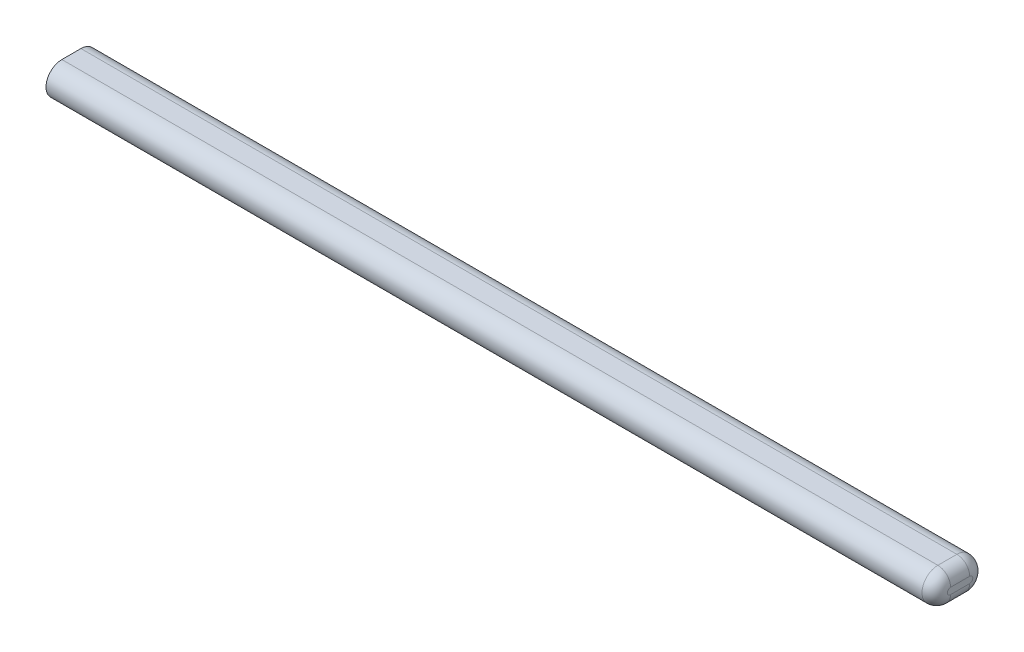
SolidWorks part; units mm, degrees
material "Mahogany"
ref_plane "Front Plane" through (0, 0, 0) normal (0, 0, 1) x (1, 0, 0)
ref_plane "Top Plane" through (0, 0, 0) normal (0, 1, 0) x (1, 0, 0)
ref_plane "Right Plane" through (0, 0, 0) normal (1, 0, 0) x (0, 0, -1)
sketch "Sketch2" plane through (0, 0, 0) normal (1, 0, 0) x (0, 0, -1)
  line L1 (7.5, 12.5) -> (-7.5, 12.5)
  line L2 (-7.5, -12.5) -> (7.5, -12.5)
  arc A0 (-7.5, 12.5) -> (-7.5, -12.5) centre (-7.5, 0) ccw
  arc A1 (7.5, 12.5) -> (7.5, -12.5) centre (7.5, 0) cw
  point P4 (0, 0)
  point P8 (0, 12.5)
  point P10 (-20, 0)
  point P11 (20, 0)
  point P12 (0, 0)
  point P13 (0, -12.5)
  dimension "D1" = 25
  dimension "D3" = 12.5
  dimension "D4" = 40
extrude "Boss-Extrude1" add sketch "Sketch2" along normal blind 700
fillet "Fillet1" radius 10 4 edges at (700, 12.5, 0) (700, 0, -20) (700, -12.5, 0) (700, 0, 20)
